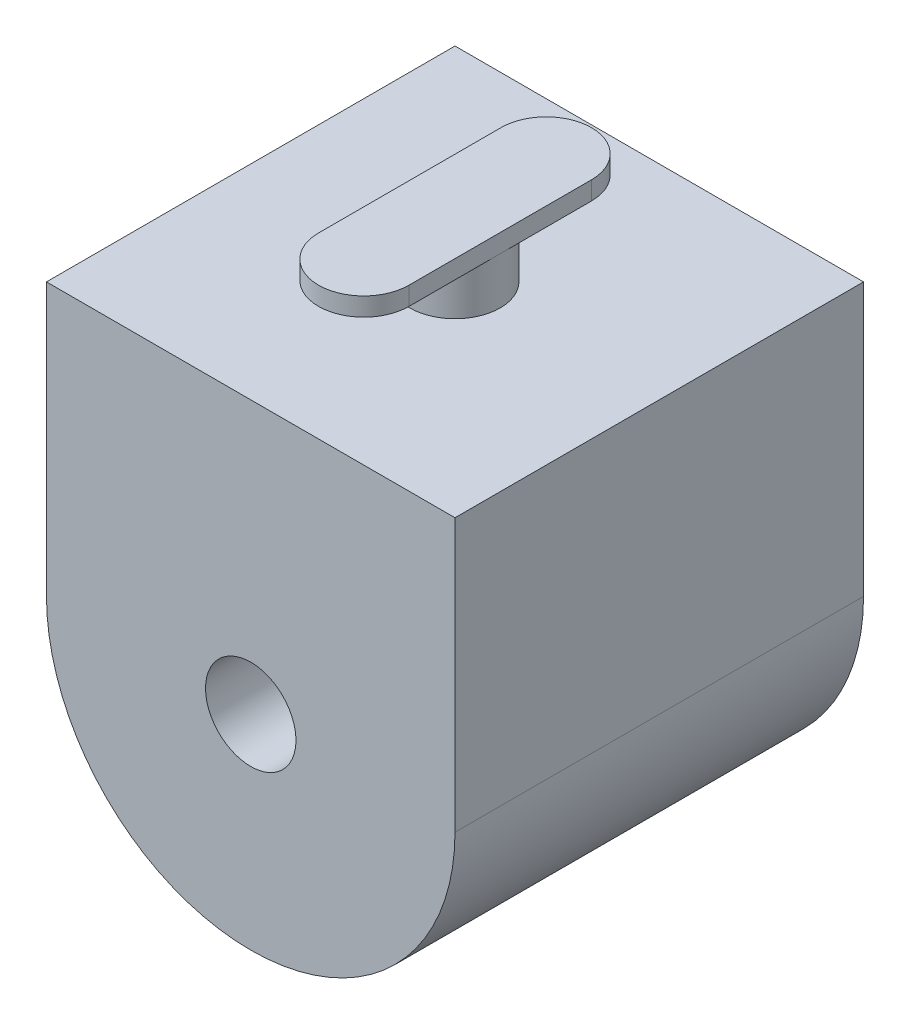
SolidWorks part; units mm, degrees
ref_plane "Front Plane" through (0, 0, 0) normal (0, 0, 1) x (1, 0, 0)
ref_plane "Top Plane" through (0, 0, 0) normal (0, 1, 0) x (1, 0, 0)
ref_plane "Right Plane" through (0, 0, 0) normal (1, 0, 0) x (0, 0, -1)
sketch "Sketch1" plane through (0, 0, 0) normal (0, 0, 1) x (1, 0, 0)
  line L2 (-19.05, -12.7) -> (-19.05, 12.7)
  line L3 (-19.05, 12.7) -> (19.05, 12.7)
  line L4 (19.05, -12.7) -> (19.05, 12.7)
  line L5 (-19.05, -12.7) -> (19.05, 12.7) construction
  line L6 (-19.05, 12.7) -> (19.05, -12.7) construction
  arc A0 (-19.05, -12.7) -> (19.05, -12.7) centre (0, -12.7) ccw
  point P0 (0, 0)
  dimension "D1" = 38.1
  dimension "D2" = 25.4
extrude "Boss-Extrude1" add sketch "Sketch1" along normal blind 38.1 contours L3 L4 A0 L2
sketch "Sketch2" plane through (0, 0, 0) normal (0, 0, -1) x (-1, 0, 0)
  circle A0 centre (0, -12.7) radius 4.2164
  dimension "D1" = 8.4328
extrude "Cut-Extrude1" cut sketch "Sketch2" against normal blind 38.1
sketch "Sketch3" plane through (0, 12.7, 0) normal (0, 1, 0) x (1, 0, 0)
  circle A0 centre (0, -19.05) radius 4.2164
  dimension "D1" = 8.4328
extrude "Boss-Extrude2" add sketch "Sketch3" along normal blind 6.096
sketch "Sketch4" plane through (0, 18.796, 0) normal (0, 1, 0) x (1, 0, 0)
  line L0 (0, -27.559) -> (0, -10.541) construction
  line L1 (-4.2164, -27.559) -> (-4.2164, -10.541)
  line L2 (4.2164, -27.559) -> (4.2164, -10.541)
  arc A0 (-4.2164, -27.559) -> (4.2164, -27.559) centre (0, -27.559) ccw
  arc A1 (4.2164, -10.541) -> (-4.2164, -10.541) centre (0, -10.541) ccw
  point P2 (0, -19.05)
  dimension "D1" = 17.018
  dimension "D2" = 8.4328
extrude "Boss-Extrude3" add sketch "Sketch4" against normal blind 1.7145
